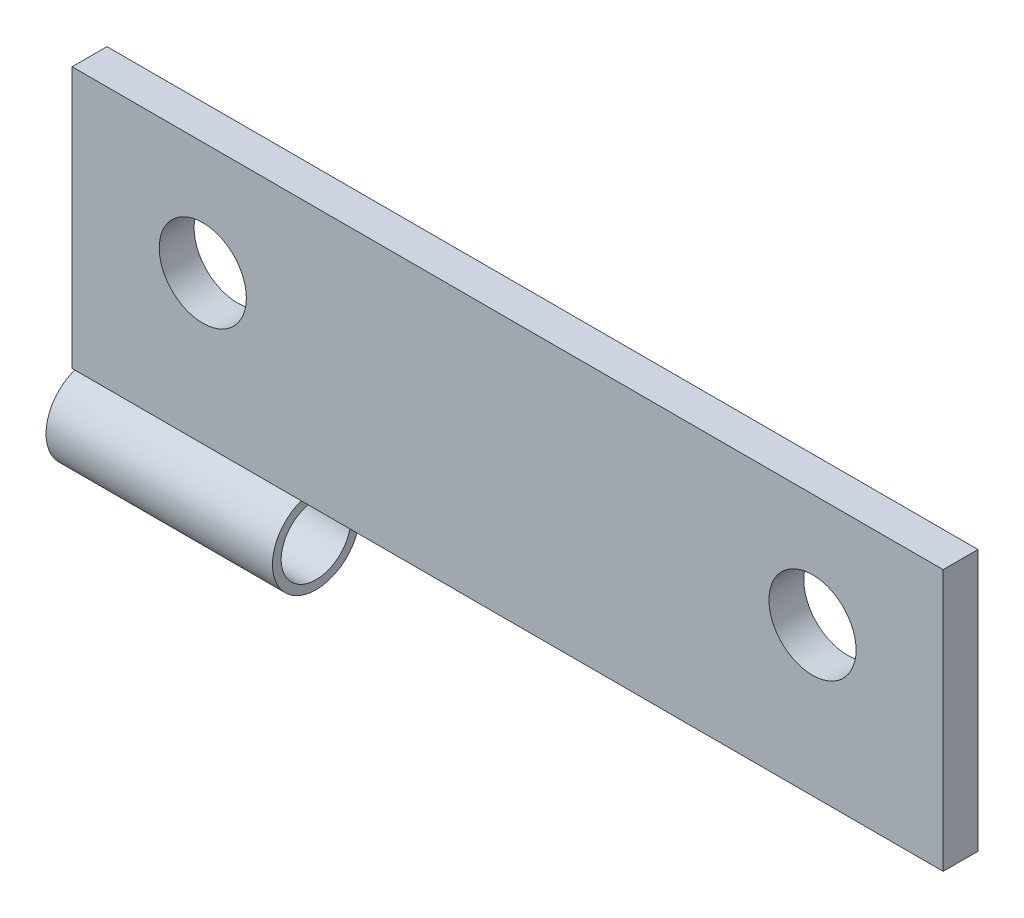
SolidWorks part; units mm, degrees
ref_plane "Plan de face" through (0, 0, 0) normal (0, 0, 1) x (1, 0, 0)
ref_plane "Plan de dessus" through (0, 0, 0) normal (0, 1, 0) x (1, 0, 0)
ref_plane "Plan de droite" through (0, 0, 0) normal (1, 0, 0) x (0, 0, -1)
sketch "Esquisse1" plane through (0, 0, 0) normal (0, 0, 1) x (1, 0, 0)
  line L1 (-6.7881, 2.8603) -> (43.2119, 2.8603)
  line L2 (-6.7881, 2.8603) -> (-6.7881, -12.1397)
  line L3 (-6.7881, -12.1397) -> (43.2119, -12.1397)
  line L4 (43.2119, 2.8603) -> (43.2119, -12.1397)
  dimension "D1" = 15
  dimension "D2" = 50
extrude "Boss.-Extru.1" add sketch "Esquisse1" against normal blind 2
sketch "Esquisse2" plane through (-6.7881, 0, 0) normal (-1, 0, 0) x (0, 0, 1)
  line L0 (-2, -12.1397) -> (0, -12.1397) construction
  circle A0 centre (-1, -14.6397) radius 2.5
  dimension "D1" = 5
extrude "Boss.-Extru.2" add sketch "Esquisse2" against normal blind 13 separate body
sketch "Esquisse3" plane through (6.2119, 0, 0) normal (1, 0, 0) x (0, 0, -1)
  circle A0 centre (1, -14.6397) radius 2
  dimension "D1" = 4
extrude "Enlèv. mat.-Extru.1" cut sketch "Esquisse3" against normal blind 9
sketch "Esquisse4" plane through (0, 0, -2) normal (0, 0, -1) x (-1, 0, 0)
  line L0 (6.7881, 2.8603) -> (6.7881, -12.1397) construction
  line L1 (-43.2119, -12.1397) -> (-43.2119, 2.8603) construction
  line L2 (-43.2119, 2.8603) -> (6.7881, 2.8603) construction
  circle A0 centre (-35.7119, -3.6397) radius 2.5
  circle A1 centre (-0.7119, -3.6397) radius 2.5
  dimension "D1" = 5
  dimension "D2" = 5
  dimension "D3" = 7.5
  dimension "D4" = 7.5
  dimension "D5" = 6.5
  dimension "D6" = 6.5
extrude "Enlèv. mat.-Extru.2" cut sketch "Esquisse4" against normal through all
